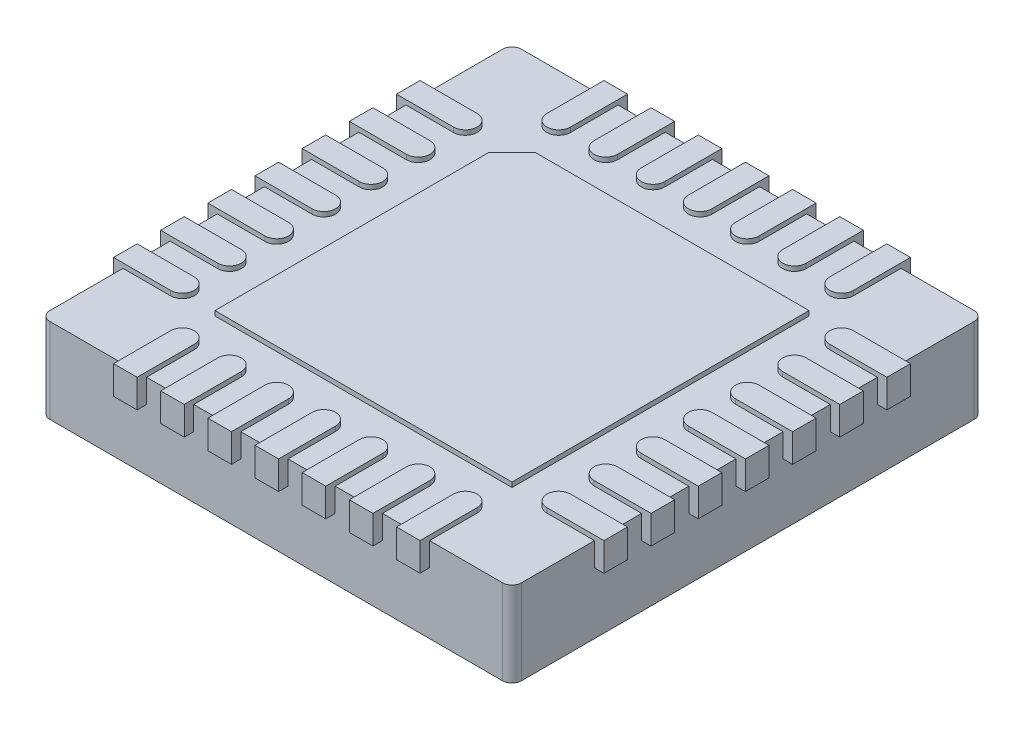
SolidWorks part; units mm, degrees
ref_plane "Front Plane" through (0, 0, 0) normal (0, 0, 1) x (1, 0, 0)
ref_plane "Top Plane" through (0, 0, 0) normal (0, 1, 0) x (1, 0, 0)
ref_plane "Right Plane" through (0, 0, 0) normal (1, 0, 0) x (0, 0, -1)
sketch "Sketch1" plane through (0, 0, 0) normal (0, 1, 0) x (1, 0, 0)
  line L0 (0, 5.3837) -> (0, -5.3605) construction
  line L1 (-7.1163, 0) -> (6.4884, 0) construction
  line L3 (2.4, -2.5) -> (-2.4, -2.5)
  line L4 (2.5, -2.4) -> (2.5, 2.4)
  line L5 (2.4, 2.5) -> (-2.4, 2.5)
  line L6 (-2.5, -2.4) -> (-2.5, 2.4)
  line L7 (2.5, -2.5) -> (-2.5, 2.5) construction
  line L8 (2.5, 2.5) -> (-2.5, -2.5) construction
  arc A0 (-2.5, -2.4) -> (-2.4, -2.5) centre (-2.4, -2.4) ccw
  arc A1 (2.4, 2.5) -> (2.5, 2.4) centre (2.4, 2.4) cw
  arc A2 (2.5, -2.4) -> (2.4, -2.5) centre (2.4, -2.4) cw
  arc A3 (-2.5, 2.4) -> (-2.4, 2.5) centre (-2.4, 2.4) cw
  point P5 (0, 0)
  dimension "D3" = 0.1
  dimension "D1" = 5
  dimension "D2" = 5
extrude "Boss-Extrude1" add sketch "Sketch1" along normal blind 0.9
sketch "Sketch3" plane through (0, 0.9, 0) normal (0, 1, 0) x (1, 0, 0)
  line L0 (-1.575, 1.3275) -> (-1.3275, 1.575)
  line L1 (1.575, -1.575) -> (-1.575, -1.575)
  line L2 (1.575, -1.575) -> (1.575, 1.575)
  line L3 (1.575, 1.575) -> (-1.3275, 1.575)
  line L4 (-1.575, -1.575) -> (-1.575, 1.3275)
  line L5 (1.575, -1.575) -> (-1.4513, 1.4513) construction
  line L6 (1.575, 1.575) -> (-1.575, -1.575) construction
  line L7 (2.4, 2.5) -> (-2.4, 2.5) construction
  line L8 (-1.625, 2.6) -> (-1.375, 2.6)
  line L9 (-1.625, 2.6) -> (-1.625, 1.995)
  line L11 (-1.375, 2.6) -> (-1.375, 1.995)
  line L12 (-0.875, 2.6) -> (-0.875, 1.995)
  line L13 (-1.125, 2.6) -> (-1.125, 1.995)
  line L14 (-1.125, 2.6) -> (-0.875, 2.6)
  line L15 (-0.375, 2.6) -> (-0.375, 1.995)
  line L16 (-0.625, 2.6) -> (-0.625, 1.995)
  line L17 (-0.625, 2.6) -> (-0.375, 2.6)
  line L18 (0.125, 2.6) -> (0.125, 1.995)
  line L19 (-0.125, 2.6) -> (-0.125, 1.995)
  line L20 (-0.125, 2.6) -> (0.125, 2.6)
  line L21 (0.625, 2.6) -> (0.625, 1.995)
  line L22 (0.375, 2.6) -> (0.375, 1.995)
  line L23 (0.375, 2.6) -> (0.625, 2.6)
  line L24 (1.125, 2.6) -> (1.125, 1.995)
  line L25 (0.875, 2.6) -> (0.875, 1.995)
  line L26 (0.875, 2.6) -> (1.125, 2.6)
  line L27 (1.625, 2.6) -> (1.625, 1.995)
  line L28 (1.375, 2.6) -> (1.375, 1.995)
  line L29 (1.375, 2.6) -> (1.625, 2.6)
  line L30 (2.5, -2.4) -> (2.5, 2.4) construction
  line L31 (0, 1.2541) -> (0, -0.9893) construction
  line L32 (-2.5, 2.4) -> (-2.5, -2.4) construction
  line L33 (-2.6, -1.375) -> (-2.6, -1.625)
  line L34 (-2.6, -1.375) -> (-1.995, -1.375)
  line L35 (-2.6, -1.625) -> (-1.995, -1.625)
  line L36 (-2.6, -0.875) -> (-2.6, -1.125)
  line L37 (-2.6, -0.875) -> (-1.995, -0.875)
  line L38 (-2.6, -1.125) -> (-1.995, -1.125)
  line L39 (-2.6, -0.375) -> (-2.6, -0.625)
  line L40 (-2.6, -0.375) -> (-1.995, -0.375)
  line L41 (-2.6, -0.625) -> (-1.995, -0.625)
  line L42 (-2.6, 0.125) -> (-2.6, -0.125)
  line L43 (-2.6, 0.125) -> (-1.995, 0.125)
  line L44 (-2.6, -0.125) -> (-1.995, -0.125)
  line L45 (-2.6, 0.625) -> (-2.6, 0.375)
  line L46 (-2.6, 0.625) -> (-1.995, 0.625)
  line L47 (-2.6, 0.375) -> (-1.995, 0.375)
  line L48 (-2.6, 1.125) -> (-2.6, 0.875)
  line L49 (-2.6, 1.125) -> (-1.995, 1.125)
  line L50 (-2.6, 0.875) -> (-1.995, 0.875)
  line L51 (-2.6, 1.625) -> (-2.6, 1.375)
  line L52 (-2.6, 1.625) -> (-1.995, 1.625)
  line L53 (-2.6, 1.375) -> (-1.995, 1.375)
  line L54 (2.6, 1.375) -> (2.6, 1.625)
  line L55 (2.6, 1.375) -> (1.995, 1.375)
  line L56 (2.6, 1.625) -> (1.995, 1.625)
  line L57 (2.6, 0.875) -> (2.6, 1.125)
  line L58 (2.6, 0.875) -> (1.995, 0.875)
  line L59 (2.6, 1.125) -> (1.995, 1.125)
  line L60 (2.6, 0.375) -> (2.6, 0.625)
  line L61 (2.6, 0.375) -> (1.995, 0.375)
  line L62 (2.6, 0.625) -> (1.995, 0.625)
  line L63 (2.6, -0.125) -> (2.6, 0.125)
  line L64 (2.6, -0.125) -> (1.995, -0.125)
  line L65 (2.6, 0.125) -> (1.995, 0.125)
  line L66 (2.6, -0.625) -> (2.6, -0.375)
  line L67 (2.6, -0.625) -> (1.995, -0.625)
  line L68 (2.6, -0.375) -> (1.995, -0.375)
  line L69 (2.6, -1.125) -> (2.6, -0.875)
  line L70 (2.6, -1.125) -> (1.995, -1.125)
  line L71 (2.6, -0.875) -> (1.995, -0.875)
  line L72 (2.6, -1.625) -> (2.6, -1.375)
  line L73 (2.6, -1.625) -> (1.995, -1.625)
  line L74 (2.6, -1.375) -> (1.995, -1.375)
  line L75 (1.625, -2.6) -> (1.625, -1.995)
  line L76 (1.375, -2.6) -> (1.375, -1.995)
  line L77 (1.625, -2.6) -> (1.375, -2.6)
  line L78 (1.125, -2.6) -> (1.125, -1.995)
  line L79 (0.875, -2.6) -> (0.875, -1.995)
  line L80 (1.125, -2.6) -> (0.875, -2.6)
  line L81 (0.625, -2.6) -> (0.625, -1.995)
  line L82 (0.375, -2.6) -> (0.375, -1.995)
  line L83 (0.625, -2.6) -> (0.375, -2.6)
  line L84 (0.125, -2.6) -> (0.125, -1.995)
  line L85 (-0.125, -2.6) -> (-0.125, -1.995)
  line L86 (0.125, -2.6) -> (-0.125, -2.6)
  line L87 (-0.375, -2.6) -> (-0.375, -1.995)
  line L88 (-0.625, -2.6) -> (-0.625, -1.995)
  line L89 (-0.375, -2.6) -> (-0.625, -2.6)
  line L90 (-0.875, -2.6) -> (-0.875, -1.995)
  line L91 (-1.125, -2.6) -> (-1.125, -1.995)
  line L92 (-0.875, -2.6) -> (-1.125, -2.6)
  line L93 (-1.375, -2.6) -> (-1.375, -1.995)
  line L94 (-1.625, -2.6) -> (-1.625, -1.995)
  line L95 (-1.375, -2.6) -> (-1.625, -2.6)
  line L96 (-2.4, -2.5) -> (2.4, -2.5) construction
  arc A0 (-1.625, 1.995) -> (-1.375, 1.995) centre (-1.5, 1.995) ccw
  arc A1 (-1.125, 1.995) -> (-0.875, 1.995) centre (-1, 1.995) ccw
  arc A2 (-0.625, 1.995) -> (-0.375, 1.995) centre (-0.5, 1.995) ccw
  arc A3 (-0.125, 1.995) -> (0.125, 1.995) centre (0, 1.995) ccw
  arc A4 (0.375, 1.995) -> (0.625, 1.995) centre (0.5, 1.995) ccw
  arc A5 (0.875, 1.995) -> (1.125, 1.995) centre (1, 1.995) ccw
  arc A6 (1.375, 1.995) -> (1.625, 1.995) centre (1.5, 1.995) ccw
  arc A7 (-1.995, -1.375) -> (-1.995, -1.625) centre (-1.995, -1.5) cw
  arc A8 (-1.995, -0.875) -> (-1.995, -1.125) centre (-1.995, -1) cw
  arc A9 (-1.995, -0.375) -> (-1.995, -0.625) centre (-1.995, -0.5) cw
  arc A10 (-1.995, 0.125) -> (-1.995, -0.125) centre (-1.995, 0) cw
  arc A11 (-1.995, 0.625) -> (-1.995, 0.375) centre (-1.995, 0.5) cw
  arc A12 (-1.995, 1.125) -> (-1.995, 0.875) centre (-1.995, 1) cw
  arc A13 (-1.995, 1.625) -> (-1.995, 1.375) centre (-1.995, 1.5) cw
  arc A14 (1.995, 1.375) -> (1.995, 1.625) centre (1.995, 1.5) cw
  arc A15 (1.995, 0.875) -> (1.995, 1.125) centre (1.995, 1) cw
  arc A16 (1.995, 0.375) -> (1.995, 0.625) centre (1.995, 0.5) cw
  arc A17 (1.995, -0.125) -> (1.995, 0.125) centre (1.995, 0) cw
  arc A18 (1.995, -0.625) -> (1.995, -0.375) centre (1.995, -0.5) cw
  arc A19 (1.995, -1.125) -> (1.995, -0.875) centre (1.995, -1) cw
  arc A20 (1.995, -1.625) -> (1.995, -1.375) centre (1.995, -1.5) cw
  arc A21 (1.625, -1.995) -> (1.375, -1.995) centre (1.5, -1.995) ccw
  arc A22 (1.125, -1.995) -> (0.875, -1.995) centre (1, -1.995) ccw
  arc A23 (0.625, -1.995) -> (0.375, -1.995) centre (0.5, -1.995) ccw
  arc A24 (0.125, -1.995) -> (-0.125, -1.995) centre (0, -1.995) ccw
  arc A25 (-0.375, -1.995) -> (-0.625, -1.995) centre (-0.5, -1.995) ccw
  arc A26 (-0.875, -1.995) -> (-1.125, -1.995) centre (-1, -1.995) ccw
  arc A27 (-1.375, -1.995) -> (-1.625, -1.995) centre (-1.5, -1.995) ccw
  point P0 (0, 0)
  point P10 (1.625, 2.5)
  point P52 (1.625, -2.5)
  point P158 (1.5, -1.87)
  dimension "D7" = 0.605
  dimension "D2" = 0.125
  dimension "D3" = 0.35
  dimension "D4" = 135
  dimension "D5" = 0.1
  dimension "D6" = 0.25
  dimension "D9" = 0.875
  dimension "D10" = 3.15
  dimension "D11" = 0.875
  dimension "D12" = 0.25
  dimension "D13" = 0.5
  dimension "D14" = 0.35
  dimension "D8" = 7
extrude "Boss-Extrude2" add sketch "Sketch3" against normal blind 0.25 and the other way blind 0.05
sketch "Sketch4" plane through (0, 0, 0) normal (0, -1, 0) x (1, 0, 0)
  line L0 (2.5, 2.4) -> (2.5, -2.4) construction
  line L1 (-0.215, 0) -> (0.2867, 0) construction
  line L2 (-2.5, 0.3763) -> (2.5, 0.3763) construction
  line L3 (-2.5, -2.4) -> (-2.5, 2.4) construction
  text T0 "QFN28" font "Century Gothic" height 1
extrude "Boss-Extrude4" add sketch "Sketch4" along normal blind 0.01
